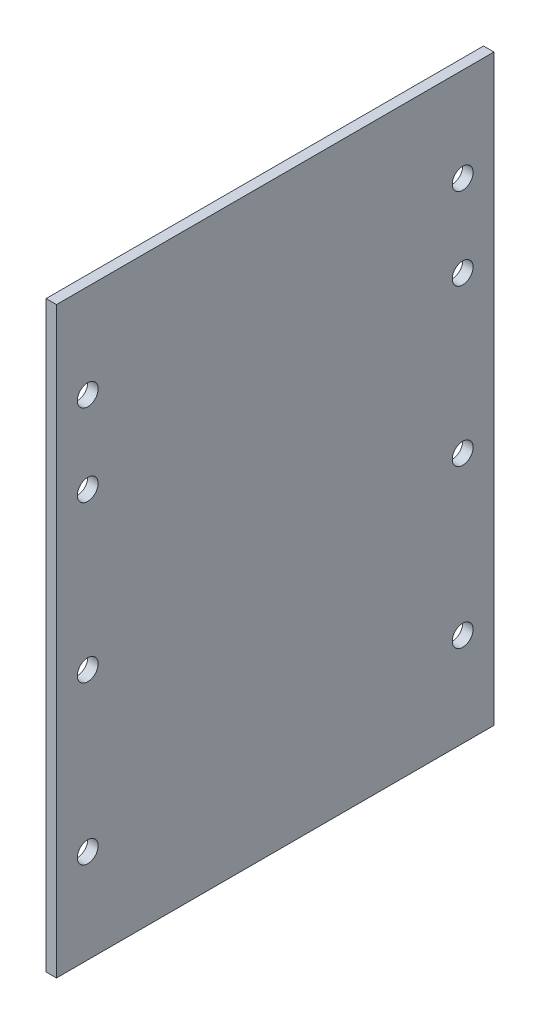
SolidWorks part; units mm, degrees
material "6061-T6 (SS)"
ref_plane "Front Plane" through (0, 0, 0) normal (0, 0, 1) x (1, 0, 0)
ref_plane "Top Plane" through (0, 0, 0) normal (0, 1, 0) x (1, 0, 0)
ref_plane "Right Plane" through (0, 0, 0) normal (1, 0, 0) x (0, 0, -1)
sketch "Sketch1" plane through (0, 0, 0) normal (1, 0, 0) x (0, 0, -1)
  line L1 (-66.675, -88.9) -> (66.675, -88.9)
  line L2 (-66.675, -88.9) -> (-66.675, 88.9)
  line L3 (-66.675, 88.9) -> (66.675, 88.9)
  line L4 (66.675, -88.9) -> (66.675, 88.9)
  line L5 (-66.675, -88.9) -> (66.675, 88.9) construction
  line L6 (-66.675, 88.9) -> (66.675, -88.9) construction
  point P0 (0, 0)
  dimension "D1" = 133.35
  dimension "D2" = 177.8
extrude "Boss-Extrude1" add sketch "Sketch1" against normal blind 3.175 contours L3 L4 L1 L2
sketch "Sketch2" plane through (0, 0, 0) normal (1, 0, 0) x (0, 0, -1)
  line L1 (-66.675, -88.9) -> (66.675, -88.9) construction
  line L2 (0, 0) -> (0, -88.9) construction
  line L3 (-66.675, 88.9) -> (66.675, 88.9) construction
  line L6 (-66.675, -88.9) -> (-66.675, 88.9) construction
  circle A24 centre (-57.15, -60.325) radius 3.175
  circle A32 centre (-57.15, -12.275) radius 3.175
  circle A33 centre (57.15, -12.275) radius 3.175
  circle A34 centre (57.15, -60.325) radius 3.175
  circle A39 centre (-57.15, 60.325) radius 3.175
  circle A40 centre (-57.15, 35.35) radius 3.175
  circle A41 centre (57.15, 35.35) radius 3.175
  circle A42 centre (57.15, 60.325) radius 3.175
  dimension "D2" = 9.525
  dimension "D4" = 6.35
  dimension "D1" = 6.35
  dimension "D5" = 6.35
  dimension "D7" = 48.05
  dimension "D9" = 47.625
  dimension "0.25" = 6.35
  dimension "D3" = 0
  dimension "D6" = 28.575
  dimension "D8" = 28.575
  dimension "D10" = 9.525
  dimension "D11" = 9.525
extrude "Cut-Extrude1" cut sketch "Sketch2" against normal through all
